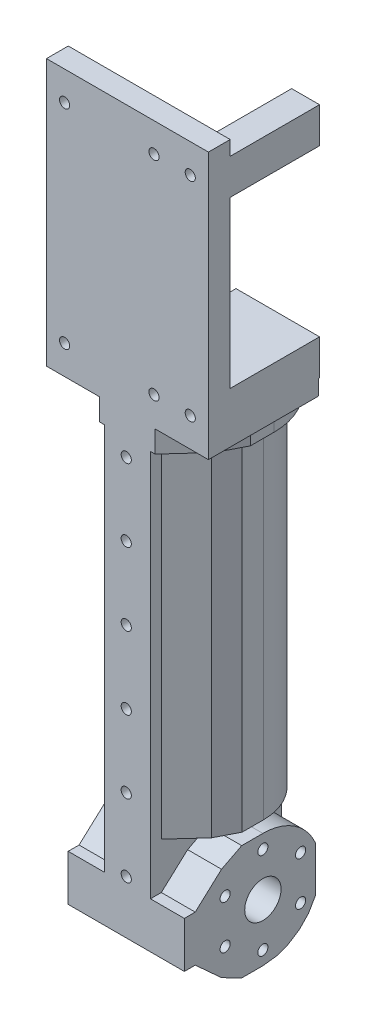
SolidWorks part; units mm, degrees
ref_plane "Plan de face" through (0, 0, 0) normal (0, 0, 1) x (1, 0, 0)
ref_plane "Plan de dessus" through (0, 0, 0) normal (0, 1, 0) x (1, 0, 0)
ref_plane "Plan de droite" through (0, 0, 0) normal (1, 0, 0) x (0, 0, -1)
sketch "Esquisse1" plane through (0, 0, 0) normal (0, 0, 1) x (1, 0, 0)
  line L0 (22.3, 30.8262) -> (0, 30.8262) construction
  line L1 (0, 0) -> (22.3, 0)
  line L2 (0, 0) -> (0, 36.68)
  line L3 (0, 36.68) -> (22.3, 36.68)
  line L4 (22.3, 0) -> (22.3, 36.68)
  line L5 (22.3, 18.34) -> (0, 18.34) construction
  line L6 (11.15, 36.68) -> (11.15, 0) construction
  line L8 (19.8, 32.68) -> (14.8, 32.68) construction
  circle A0 centre (19.8, 32.68) radius 0.7
  circle A1 centre (2.5, 32.68) radius 0.7
  circle A2 centre (2.5, 4) radius 0.7
  circle A3 centre (19.8, 4) radius 0.7
  circle A4 centre (14.8, 32.68) radius 0.7
  circle A5 centre (14.8, 4) radius 0.7
  dimension "D3" = 2.5
  dimension "D5" = 5
  dimension "D1" = 36.68
  dimension "D2" = 22.3
  dimension "D4" = 4
extrude "Boss.-Extru.1" add sketch "Esquisse1" along normal blind 3
sketch "Esquisse2" plane through (0, 0, 0) normal (0, 0, -1) x (-1, 0, 0)
  line L0 (0, 0) -> (-22.3, 0) construction
  line L5 (-22.3, 2.1) -> (-10.8, 2.1)
  line L6 (-22.3, 2.1) -> (-22.3, 7)
  line L7 (-22.3, 7) -> (-10.8, 7)
  line L8 (-10.8, 2.1) -> (-10.8, 7)
  line L10 (-22.3, 0) -> (-22.3, 36.68) construction
  dimension "D2" = 4.9
  dimension "D3" = 2.1
  dimension "D5" = 11.5
extrude "Boss.-Extru.2" add sketch "Esquisse2" along normal blind 12.3
sketch "Esquisse3" plane through (0, 0, 3) normal (0, 0, 1) x (1, 0, 0)
  circle A0 centre (14.8, 32.68) radius 0.7
  circle A1 centre (19.8, 32.68) radius 0.7
  circle A2 centre (14.8, 4) radius 0.7
  circle A3 centre (19.8, 4) radius 0.7
extrude "Enlèv. mat.-Extru.1" cut sketch "Esquisse3" against normal through all
sketch "Esquisse4" plane through (0, 2.1, 0) normal (0, -1, 0) x (1, 0, 0)
  line L0 (22.3, 0) -> (10.8449, 0)
  line L1 (22.3, 0) -> (10.8, 0) construction
  line L2 (10.8449, 0) -> (22.3, -12.1821)
  line L3 (22.3, -12.3) -> (22.3, 0) construction
  line L4 (22.3, -12.1821) -> (22.3, 0)
extrude "Boss.-Extru.3" add sketch "Esquisse4" along normal blind 2.1
sketch "Esquisse6" plane through (0, 0, 0) normal (0, -1, 0) x (1, 0, 0)
  line L0 (11.15, 3) -> (11.15, 0.6955) construction
  line L1 (0, 3) -> (22.3, 3) construction
  line L2 (14.9775, 3) -> (7.3225, 3)
  line L3 (7.3225, 3) -> (3.4412, -1.2584)
  line L4 (3.4412, -1.2584) -> (1.7562, -4.5369)
  line L5 (1.7562, -4.5369) -> (1.7562, -7.8132)
  line L6 (11.15, 3) -> (11.15, -28.056) construction
  line L7 (20.5438, -4.5369) -> (20.5438, -7.8132)
  line L8 (18.8588, -1.2584) -> (20.5438, -4.5369)
  line L9 (14.9775, 3) -> (18.8588, -1.2584)
  circle A0 centre (1.7562, -7.8132) radius 9.3938 construction
  arc A1 (1.7562, -7.8132) -> (20.5438, -7.8132) centre (11.15, -7.8132) ccw
extrude "Boss.-Extru.4" add sketch "Esquisse6" along normal blind 3
sketch "Esquisse8" plane through (0, -3, 0) normal (0, -1, 0) x (1, 0, 0)
  line L0 (14.9775, 3) -> (7.3225, 3) construction
  line L1 (7.3225, 3) -> (4.5882, 0) construction
  line L2 (7.3225, 3) -> (3.4412, -1.2584) construction
  line L3 (3.4412, -1.2584) -> (1.7562, -4.5369) construction
  line L4 (7.3225, 3) -> (3.4412, -1.2584) construction
  line L5 (3.4412, -1.2584) -> (1.7562, -4.5369) construction
  line L6 (1.7562, -4.5369) -> (1.7562, -7.8132) construction
  line L7 (1.7562, -7.8132) -> (11.15, -7.8132) construction
  line L8 (11.15, -7.8132) -> (11.15, 3) construction
  line L9 (11.15, -7.8132) -> (11.15, -19.9925) construction
  line L10 (14.9775, 3) -> (7.3225, 3) construction
  line L11 (20.5438, -4.5369) -> (20.5438, -7.8132) construction
  line L12 (18.8588, -1.2584) -> (20.5438, -4.5369) construction
  line L13 (14.9775, 3) -> (18.8588, -1.2584) construction
  line L15 (7.9849, 1.5) -> (4.6842, -2.1215)
  line L16 (4.6842, -2.1215) -> (3.2562, -4.8999)
  line L17 (3.2562, -4.8999) -> (3.2562, -7.8132)
  line L18 (19.0438, -4.8999) -> (19.0438, -7.8132)
  line L19 (17.6158, -2.1215) -> (19.0438, -4.8999)
  line L20 (14.3151, 1.5) -> (17.6158, -2.1215)
  line L21 (7.9849, 1.5) -> (7.9849, 3)
  line L22 (7.9849, 3) -> (14.3151, 3)
  line L23 (8.4311, 1.9896) -> (4.6842, -2.1215) construction
  line L24 (14.3151, 3) -> (14.3151, 1.5)
  line L26 (13.8689, 1.9896) -> (17.6158, -2.1215) construction
  arc A0 (1.7562, -7.8132) -> (20.5438, -7.8132) centre (11.15, -7.8132) ccw construction
  arc A1 (3.2562, -7.8132) -> (19.0438, -7.8132) centre (11.15, -7.8132) ccw
  point P20 (14.9775, 1.5)
  point P21 (7.3225, 1.5)
  dimension "D1" = 1.5
extrude "Boss.-Extru.5" add sketch "Esquisse8" along normal blind 47
sketch "Esquisse9" plane through (0, -50, 0) normal (0, -1, 0) x (1, 0, 0)
  line L0 (7.9849, 3) -> (7.9849, -15.0447)
  line L1 (7.9849, 3) -> (14.3151, 3)
  line L2 (14.3151, 3) -> (14.3151, -15.0447)
  line L3 (14.3151, -15.0447) -> (7.9849, -15.0447)
  arc A0 (3.2562, -7.8132) -> (19.0438, -7.8132) centre (11.15, -7.8132) ccw construction
extrude "Boss.-Extru.6" add sketch "Esquisse9" along normal blind 19
sketch "Esquisse10" plane through (7.9849, 0, 0) normal (-1, 0, 0) x (0, 0, 1)
  line L0 (3, -69) -> (3, -3) construction
  line L6 (3, -3) -> (1.5, -3)
  line L7 (1.5, -3) -> (1.5, -50)
  line L8 (1.5, -50) -> (-15.0447, -50)
  line L9 (-15.0447, -50) -> (-15.0447, -69)
  line L10 (-15.0447, -69) -> (3, -69)
  line L11 (3, -69) -> (3, -3)
  line L12 (3, -3) -> (1.5, -3)
  line L13 (1.5, -3) -> (1.5, -50)
  line L14 (1.5, -50) -> (-15.0447, -50)
  line L15 (-15.0447, -50) -> (-15.0447, -69)
  line L16 (-15.0447, -69) -> (3, -69)
  line L17 (3, -69) -> (3, -3)
  line B0 (3, -63.3543) -> (3, -55.6993) construction
  line B1 (3, -55.6993) -> (-1.2584, -51.818) construction
  line B2 (-1.2584, -51.818) -> (-4.5369, -50.133) construction
  line B3 (-4.5369, -50.133) -> (-7.8132, -50.133) construction
  line B4 (-7.8132, -50.133) -> (-7.8132, -59.5268) construction
  line B5 (-7.8132, -59.5268) -> (3, -59.5268) construction
  line B6 (-7.8132, -59.5268) -> (-19.9925, -59.5268) construction
  line B7 (3, -63.3543) -> (3, -55.6993) construction
  line B8 (-4.5369, -68.9206) -> (-7.8132, -68.9206) construction
  line B9 (-1.2584, -67.2356) -> (-4.5369, -68.9206) construction
  line B10 (3, -63.3543) -> (-1.2584, -67.2356) construction
  line B11 (1.5, -56.3617) -> (-2.1215, -53.061)
  line B12 (-2.1215, -53.061) -> (-4.8999, -51.633)
  line B13 (-4.8999, -51.633) -> (-7.8132, -51.633)
  line B14 (-4.8999, -67.4206) -> (-7.8132, -67.4206)
  line B15 (-2.1215, -65.9926) -> (-4.8999, -67.4206)
  line B16 (1.5, -62.6919) -> (-2.1215, -65.9926)
  line B17 (1.5, -56.3617) -> (3, -56.3617)
  line B18 (3, -56.3617) -> (3, -62.6919)
  line B19 (3, -62.6919) -> (1.5, -62.6919)
  arc B20 (-7.8132, -50.133) -> (-7.8132, -68.9206) centre (-7.8132, -59.5268) ccw construction
  arc B21 (-7.8132, -51.633) -> (-7.8132, -67.4206) centre (-7.8132, -59.5268) ccw
  dimension "D1" = 0
sketch_block_instance "Bloc1-1"
sketch_block "Bloc1"
extrude "Boss.-Extru.7" add sketch "Esquisse10" along normal blind 5 and the other way blind 11 contours B13 B21 L15 B14 B15 B16 B19 B18 B17 B11 B12
sketch "Esquisse12" plane through (7.9849, 0, 0) normal (-1, 0, 0) x (0, 0, 1)
  line L0 (-15.0447, -62.6919) -> (-15.0447, -69)
  line L1 (-15.0447, -69) -> (3, -69)
  line L2 (3, -69) -> (3, -62.6919)
  line L3 (3, -62.6919) -> (1.5, -62.6919)
  line L4 (1.5, -62.6919) -> (-2.1215, -65.9926)
  line L5 (-2.1215, -65.9926) -> (-4.8999, -67.4206)
  line L6 (-4.8999, -67.4206) -> (-7.8132, -67.4206)
  line L7 (-7.8132, -67.4206) -> (-9.6863, -67.1952)
  line L8 (-9.6863, -67.1952) -> (-11.2323, -66.6417)
  line L9 (-11.2323, -66.6417) -> (-12.8005, -65.6456)
  line L10 (-12.8005, -65.6456) -> (-14.0681, -64.3423)
  line L11 (-14.0681, -64.3423) -> (-15.0447, -62.6919)
  arc A0 (-15.0447, -62.6919) -> (-7.8132, -67.4206) centre (-7.8132, -59.5268) ccw construction
  arc A1 (-15.0447, -62.6919) -> (-7.8132, -67.4206) centre (-7.8132, -59.5268) ccw construction
extrude "Enlèv. mat.-Extru.3" cut sketch "Esquisse12" against normal through all and the other way through all
sketch "Esquisse13" plane through (0, 0, 3) normal (0, 0, 1) x (1, 0, 0)
  line L0 (10.9849, -62.6919) -> (10.9849, 0) construction
  line L1 (18.9849, -62.6919) -> (2.9849, -62.6919) construction
  circle A0 centre (10.9849, -5.3697) radius 0.7
  circle A1 centre (10.9849, -15.3697) radius 0.7
  circle A2 centre (10.9849, -25.3697) radius 0.7
  circle A3 centre (10.9849, -35.3697) radius 0.7
  circle A4 centre (10.9849, -45.3697) radius 0.7
  circle A5 centre (10.9849, -55.3697) radius 0.7
  dimension "D1" = 6
extrude "Enlèv. mat.-Extru.4" cut sketch "Esquisse13" against normal blind 10
sketch "Esquisse15" plane through (2.9849, 0, 0) normal (-1, 0, 0) x (0, 0, 1)
  line L0 (-7.8132, -51.633) -> (-7.8132, -67.4206) construction
  line L1 (-15.0447, -59.5268) -> (-7.8132, -59.5268) construction
  line L2 (-15.0447, -56.3617) -> (-15.0447, -62.6919) construction
  circle A0 centre (-7.8132, -59.5268) radius 2.5
  circle A1 centre (-7.8132, -53.5268) radius 0.7
  circle A2 centre (-2.617, -56.5268) radius 0.7
  circle A3 centre (-2.617, -62.5268) radius 0.7
  circle A4 centre (-7.8132, -65.5268) radius 0.7
  circle A5 centre (-13.0093, -62.5268) radius 0.7
  circle A6 centre (-13.0093, -56.5268) radius 0.7
  point P23 (-7.8132, -59.5268)
  dimension "D1" = 6
  dimension "D2" = 6
extrude "Enlèv. mat.-Extru.5" cut sketch "Esquisse15" against normal through all
sketch "Esquisse16" plane through (0, 0, 0) normal (0, 0, -1) x (-1, 0, 0)
  line L0 (-22.3, 7) -> (-22.3, 36.68) construction
  line L1 (-22.3, 34.68) -> (-10.8, 34.68)
  line L2 (-22.3, 34.68) -> (-22.3, 29.78)
  line L3 (-22.3, 29.78) -> (-10.8, 29.78)
  line L4 (-10.8, 34.68) -> (-10.8, 29.78)
  line L5 (-22.3, 36.68) -> (0, 36.68) construction
  dimension "D1" = 2
  dimension "D2" = 11.5
  dimension "D3" = 4.9
extrude "Boss.-Extru.8" add sketch "Esquisse16" along normal blind 12.3
sketch "Esquisse17" plane through (0, 0, 3) normal (0, 0, 1) x (1, 0, 0)
  circle A0 centre (14.8, 32.68) radius 0.7
  circle A1 centre (19.8, 32.68) radius 0.7
extrude "Enlèv. mat.-Extru.6" cut sketch "Esquisse17" against normal through all
sketch "Esquisse18" plane through (0, 34.68, 0) normal (0, 1, 0) x (1, 0, 0)
  line L1 (10.8, 12.3) -> (18.4638, 12.3)
  line L2 (10.8, 12.3) -> (10.8, 0.8689)
  line L3 (10.8, 0.8689) -> (18.4638, 0.8689)
  line L4 (18.4638, 12.3) -> (18.4638, 0.8689)
extrude "Enlèv. mat.-Extru.7" cut sketch "Esquisse18" against normal blind 6.3
